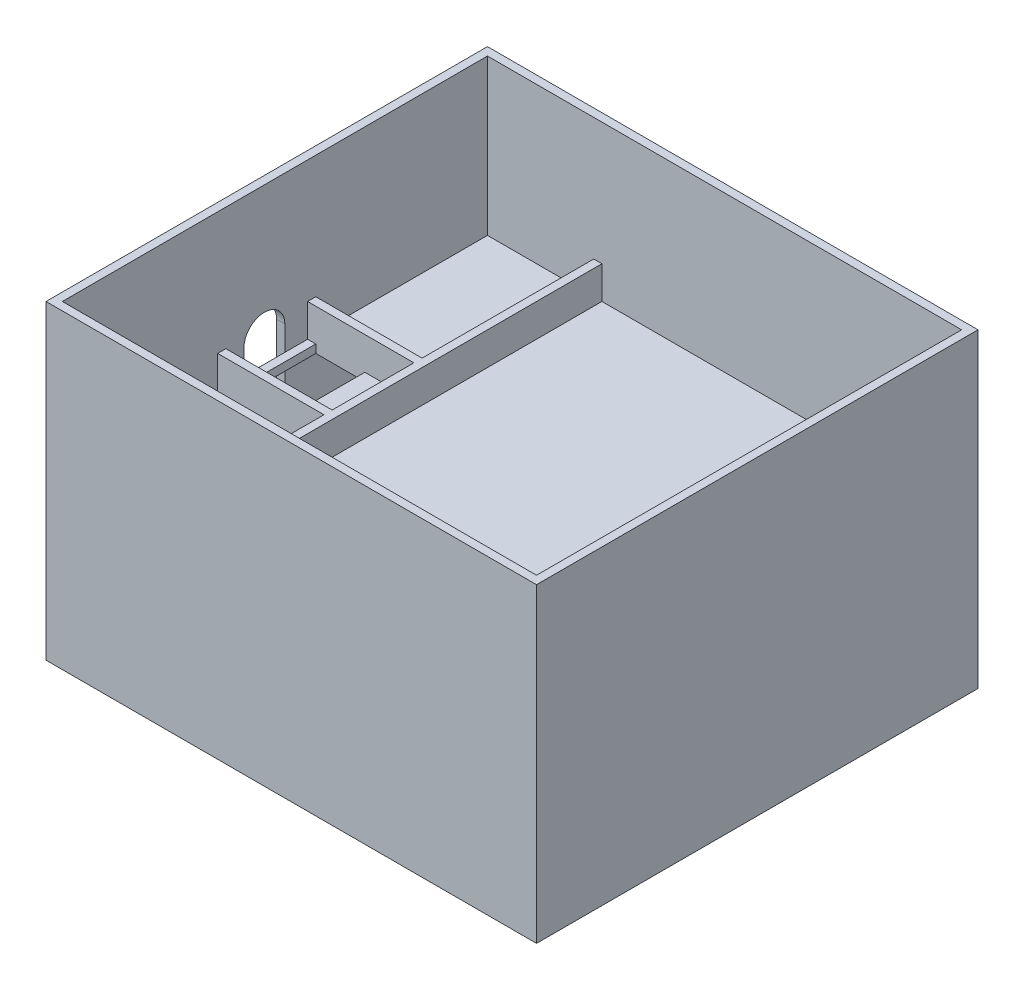
SolidWorks part; units mm, degrees
ref_plane "Front Plane" through (0, 0, 0) normal (0, 0, 1) x (1, 0, 0)
ref_plane "Top Plane" through (0, 0, 0) normal (0, 1, 0) x (1, 0, 0)
ref_plane "Right Plane" through (0, 0, 0) normal (1, 0, 0) x (0, 0, -1)
sketch "Sketch1" plane through (0, 0, 0) normal (0, 1, 0) x (1, 0, 0)
  line L1 (-113.8745, -60.9464) -> (-53.8745, -60.9464)
  line L2 (-113.8745, -60.9464) -> (-113.8745, -6.9464)
  line L3 (-113.8745, -6.9464) -> (-53.8745, -6.9464)
  line L4 (-53.8745, -60.9464) -> (-53.8745, -6.9464)
  dimension "D1" = 60
  dimension "D2" = 54
extrude "Boss-Extrude1" add sketch "Sketch1" along normal blind 38
sketch "Sketch2" plane through (0, 38, 0) normal (0, 1, 0) x (1, 0, 0)
  line L0 (-53.8745, -60.9464) -> (-53.8745, -6.9464) construction
  line L1 (-54.8745, -7.9464) -> (-98.8745, -7.9464)
  line L2 (-54.8745, -7.9464) -> (-54.8745, -59.9464)
  line L3 (-54.8745, -59.9464) -> (-98.8745, -59.9464)
  line L4 (-98.8745, -7.9464) -> (-98.8745, -59.9464)
  line L5 (-53.8745, -6.9464) -> (-113.8745, -6.9464) construction
  line L6 (-113.8745, -60.9464) -> (-53.8745, -60.9464) construction
  dimension "D1" = 1
  dimension "D2" = 1
  dimension "D3" = 1
  dimension "D4" = 44
extrude "Cut-Extrude1" cut sketch "Sketch2" against normal blind 19
sketch "Sketch3" plane through (0, 0, 0) normal (0, -1, 0) x (-1, 0, 0)
  line L0 (113.8745, -60.9464) -> (53.8745, -60.9464) construction
  line L1 (112.8745, -59.9464) -> (77.8745, -59.9464)
  line L2 (112.8745, -59.9464) -> (112.8745, -7.9464)
  line L3 (112.8745, -7.9464) -> (77.8745, -7.9464)
  line L4 (77.8745, -59.9464) -> (77.8745, -7.9464)
  line L5 (113.8745, -6.9464) -> (113.8745, -60.9464) construction
  line L6 (53.8745, -6.9464) -> (113.8745, -6.9464) construction
  dimension "D1" = 1
  dimension "D2" = 35
  dimension "D3" = 1
  dimension "D4" = 1
extrude "Cut-Extrude2" cut sketch "Sketch3" against normal blind 18
sketch "Sketch4" plane through (0, 18, 0) normal (0, -1, 0) x (-1, 0, 0)
  line L0 (77.8745, -59.9464) -> (112.8745, -59.9464) construction
  line L1 (111.8745, -39.9464) -> (105.8745, -39.9464)
  line L2 (111.8745, -39.9464) -> (111.8745, -29.9464)
  line L3 (111.8745, -29.9464) -> (105.8745, -29.9464)
  line L4 (105.8745, -39.9464) -> (105.8745, -29.9464)
  line L5 (112.8745, -7.9464) -> (77.8745, -7.9464) construction
  line L6 (112.8745, -59.9464) -> (112.8745, -7.9464) construction
  dimension "D1" = 20
  dimension "D2" = 22
  dimension "D3" = 1
  dimension "D4" = 6
extrude "Cut-Extrude3" cut sketch "Sketch4" against normal blind 38
sketch "Sketch5" plane through (0, 38, 0) normal (0, 1, 0) x (1, 0, 0)
  line L0 (-53.8745, -6.9464) -> (-113.8745, -6.9464) construction
  line L1 (-98.8745, -59.9464) -> (-112.8745, -59.9464)
  line L2 (-98.8745, -59.9464) -> (-98.8745, -7.9464)
  line L3 (-98.8745, -7.9464) -> (-112.8745, -7.9464)
  line L4 (-112.8745, -59.9464) -> (-112.8745, -7.9464)
  line L5 (-113.8745, -6.9464) -> (-113.8745, -60.9464) construction
  dimension "D1" = 1
  dimension "D2" = 1
extrude "Cut-Extrude5" cut sketch "Sketch5" against normal blind 15
sketch "Sketch6" plane through (0, 23, 0) normal (0, 1, 0) x (1, 0, 0)
  line L0 (-112.8745, -59.9464) -> (-98.8745, -59.9464) construction
  line L1 (-112.8745, -7.9464) -> (-99.8745, -7.9464)
  line L2 (-112.8745, -7.9464) -> (-112.8745, -59.9464)
  line L3 (-112.8745, -59.9464) -> (-99.8745, -59.9464)
  line L4 (-99.8745, -7.9464) -> (-99.8745, -59.9464)
  line L5 (-98.8745, -59.9464) -> (-98.8745, -7.9464) construction
  dimension "D1" = 1
extrude "Cut-Extrude6" cut sketch "Sketch6" against normal blind 4
sketch "Sketch8" plane through (0, 0, 0) normal (0, -1, 0) x (-1, 0, 0)
  line L0 (53.8745, -60.9464) -> (53.8745, -6.9464) construction
  line L1 (73.3745, -11.4464) -> (58.3745, -11.4464)
  line L2 (73.3745, -11.4464) -> (73.3745, -24.4464)
  line L3 (73.3745, -24.4464) -> (58.3745, -24.4464)
  line L4 (58.3745, -11.4464) -> (58.3745, -24.4464)
  line L6 (53.8745, -6.9464) -> (113.8745, -6.9464) construction
  dimension "D1" = 15
  dimension "D2" = 13
  dimension "D3" = 4.5
  dimension "D4" = 4.5
extrude "Cut-Extrude7" cut sketch "Sketch8" against normal blind 6
sketch "Sketch10" plane through (-73.3745, 0, 0) normal (1, 0, 0) x (0, 0, -1)
  line L0 (-11.4464, 6) -> (-11.4464, 0) construction
  line L1 (-24.4464, 6) -> (-11.4464, 6)
  line L2 (-24.4464, 6) -> (-24.4464, 1)
  line L3 (-24.4464, 1) -> (-11.4464, 1)
  line L4 (-11.4464, 6) -> (-11.4464, 1)
  line L5 (-24.4464, 0) -> (-11.4464, 0) construction
  point P7 (-11.9162, 2.727)
  dimension "D1" = 1
extrude "Cut-Extrude8" cut sketch "Sketch10" against normal blind 6
sketch "Sketch11" plane through (0, 0, 0) normal (0, -1, 0) x (1, 0, 0)
  line L0 (-113.8745, 60.9464) -> (-53.8745, 60.9464) construction
  line L1 (-67.8745, 50.9464) -> (-63.8745, 50.9464)
  line L2 (-67.8745, 50.9464) -> (-67.8745, 45.9464)
  line L3 (-67.8745, 45.9464) -> (-63.8745, 45.9464)
  line L4 (-63.8745, 50.9464) -> (-63.8745, 45.9464)
  line L5 (-53.8745, 60.9464) -> (-53.8745, 6.9464) construction
  dimension "D1" = 4
  dimension "D2" = 5
  dimension "D3" = 10
  dimension "D4" = 10
extrude "Cut-Extrude9" cut sketch "Sketch11" against normal blind 3
sketch "Sketch12" plane through (-67.8745, 0, 0) normal (1, 0, 0) x (0, 0, -1)
  line L0 (-50.9464, 3) -> (-50.9464, 0) construction
  line L1 (-45.9464, 3) -> (-50.9464, 3)
  line L2 (-45.9464, 3) -> (-45.9464, 1)
  line L3 (-45.9464, 1) -> (-50.9464, 1)
  line L4 (-50.9464, 3) -> (-50.9464, 1)
  line L5 (-50.9464, 0) -> (-45.9464, 0) construction
  point P7 (-49.533, -3.8829)
  dimension "D1" = 1
extrude "Cut-Extrude10" cut sketch "Sketch12" against normal blind 13
sketch "Sketch13" plane through (-113.8745, 0, 0) normal (-1, 0, 0) x (0, 0, 1)
  line L0 (35.233, 15) -> (35.233, 22) construction
  line L1 (32.733, 15) -> (32.733, 22)
  line L2 (37.733, 15) -> (37.733, 22)
  line L3 (59.9464, 18) -> (7.9464, 18) construction
  line L4 (39.9464, 19) -> (29.9464, 19) construction
  arc A0 (32.733, 15) -> (37.733, 15) centre (35.233, 15) ccw
  arc A1 (37.733, 22) -> (32.733, 22) centre (35.233, 22) ccw
  point P2 (35.233, 18.5)
  point P7 (0, 0)
  point P8 (14.7226, 4.5519)
  dimension "D1" = 3
  dimension "D2" = 3
  dimension "D3" = 2.5
extrude "Cut-Extrude11" cut sketch "Sketch13" against normal blind 1
sketch "Sketch14" plane through (0, 19, 0) normal (0, 1, 0) x (1, 0, 0)
  line L0 (-99.8745, -59.9464) -> (-99.8745, -7.9464) construction
  line L1 (-112.8745, -40.9464) -> (-99.8745, -40.9464)
  line L2 (-112.8745, -40.9464) -> (-112.8745, -39.9464)
  line L3 (-112.8745, -39.9464) -> (-99.8745, -39.9464)
  line L4 (-99.8745, -40.9464) -> (-99.8745, -39.9464)
  line L5 (-112.8745, -37.733) -> (-112.8745, -59.9464) construction
  line L6 (-105.8745, -39.9464) -> (-111.8745, -39.9464) construction
  point P6 (-120.1002, -35.2386)
  point P7 (-123.1182, -45.5085)
  point P8 (-107.1478, -38.8588)
  dimension "D1" = 0
  dimension "D2" = 1
  dimension "D3" = 0
extrude "Boss-Extrude2" add sketch "Sketch14" along normal blind 4
sketch "Sketch15" plane through (0, 19, 0) normal (0, 1, 0) x (1, 0, 0)
  line L0 (-112.8745, -7.9464) -> (-112.8745, -32.733) construction
  line L1 (-112.8745, -29.9464) -> (-99.8745, -29.9464)
  line L2 (-112.8745, -29.9464) -> (-112.8745, -28.9464)
  line L3 (-112.8745, -28.9464) -> (-99.8745, -28.9464)
  line L4 (-99.8745, -29.9464) -> (-99.8745, -28.9464)
  line L5 (-99.8745, -39.9464) -> (-99.8745, -7.9464) construction
  line L6 (-111.8745, -29.9464) -> (-105.8745, -29.9464) construction
  point P8 (-103.7086, -29.8744)
  dimension "D1" = 0
  dimension "D2" = 1
extrude "Boss-Extrude3" add sketch "Sketch15" along normal blind 4
